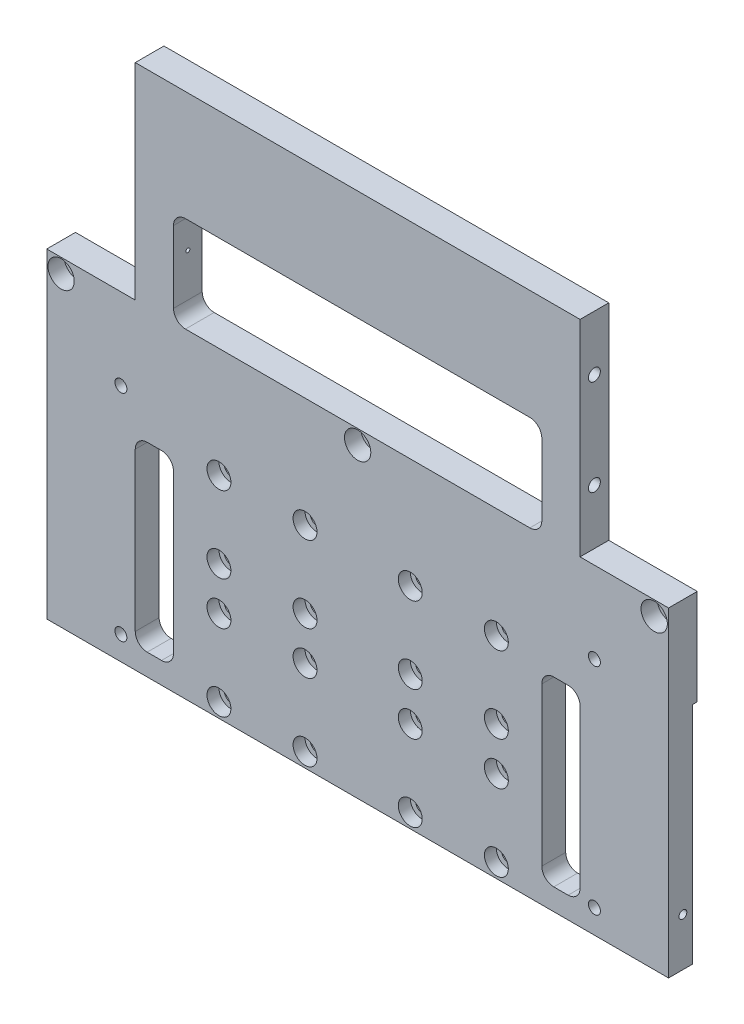
SolidWorks part; units mm, degrees
material "45#"
ref_plane "前视" through (0, 0, 0) normal (0, 0, 1) x (1, 0, 0)
ref_plane "上视" through (0, 0, 0) normal (0, 1, 0) x (1, 0, 0)
ref_plane "右视" through (0, 0, 0) normal (1, 0, 0) x (0, 0, -1)
sketch "草图1" plane through (0, 0, 0) normal (0, 0, 1) x (1, 0, 0)
  line L1 (-130, -110) -> (130, -110)
  line L2 (-130, -110) -> (-130, 110)
  line L3 (-130, 110) -> (130, 110)
  line L4 (130, -110) -> (130, 110)
  line L5 (-130, -110) -> (130, 110) construction
  line L6 (-130, 110) -> (130, -110) construction
  point P0 (0, 0)
  dimension "D1" = 260
  dimension "D2" = 220
extrude "凸台-拉伸1" add sketch "草图1" along normal blind 12
sketch "草图2" plane through (130, 0, 0) normal (1, 0, 0) x (0, 0, -1)
  line L1 (0, -110) -> (-2, -110)
  line L2 (0, -110) -> (0, -16)
  line L3 (0, -16) -> (-2, -16)
  line L4 (-2, -110) -> (-2, -16)
  dimension "D1" = 94
  dimension "D2" = 2
extrude "切除-拉伸1" cut sketch "草图2" against normal through all
hole_wizard "打孔尺寸根据内六角圆柱头螺钉的类型1" positions "草图4" profile "草图3" counterbore size "M5" standard "Gb" end condition through all
sketch "草图4" plane through (0, 0, 12) normal (0, 0, 1) x (1, 0, 0)
  line L0 (0, -16) -> (0, -63) construction
  line L1 (-130, -16) -> (130, -16) construction
  line L2 (0, -63) -> (-130, -63) construction
  line L3 (-130, 110) -> (-130, -110) construction
  point P0 (-58, -22)
  point P2 (-22, -22)
  point P4 (-22, -54)
  point P6 (-58, -54)
  point P20 (58, -54)
  point P21 (22, -54)
  point P22 (22, -22)
  point P23 (58, -22)
  point P24 (58, -104)
  point P25 (22, -104)
  point P26 (22, -72)
  point P27 (58, -72)
  point P28 (-58, -72)
  point P29 (-22, -72)
  point P30 (-22, -104)
  point P31 (-58, -104)
  dimension "D1" = 36
  dimension "D2" = 32
  dimension "D3" = 6
  dimension "D4" = 44
  dimension "D5" = 50
sketch "草图3" plane through (-58, -22, 12) normal (1, 0, 0) x (0, -1, 0)
  line L0 (0, 0) -> (0, 12)
  line L1 (0, 12) -> (2.75, 12)
  line L3 (2.75, 12) -> (2.75, 5)
  line L4 (2.75, 5) -> (5, 5)
  line L5 (5, 5) -> (5, 0)
  line L7 (5, 0) -> (0, 0)
  line L11 (0, -6.35) -> (0, 107.95) construction
  dimension "通孔孔直径" = 5.5
  dimension "通孔孔深度" = 12
  dimension "柱形沉头孔直径" = 10
  dimension "柱形沉头孔深度" = 5
hole_wizard "打孔尺寸根据内六角圆柱头螺钉的类型2" positions "草图6" profile "草图5" counterbore size "M6" standard "Gb" end condition through all
sketch "草图6" plane through (0, 0, 12) normal (0, 0, 1) x (1, 0, 0)
  line L0 (0, 110) -> (0, 24.5896) construction
  line L1 (130, 110) -> (-130, 110) construction
  line L2 (-130, 110) -> (-130, -110) construction
  line L3 (-130, -16) -> (130, -16) construction
  point P0 (-124, 18)
  point P9 (0, 18)
  point P12 (124, 18)
  dimension "D1" = 6
  dimension "D2" = 34
sketch "草图5" plane through (-124, 18, 12) normal (1, 0, 0) x (0, -1, 0)
  line L0 (0, 0) -> (0, 12)
  line L1 (0, 12) -> (3.3, 12)
  line L3 (3.3, 12) -> (3.3, 6.8)
  line L4 (3.3, 6.8) -> (5.5, 6.8)
  line L5 (5.5, 6.8) -> (5.5, 0)
  line L7 (5.5, 0) -> (0, 0)
  line L11 (0, -6.35) -> (0, 107.95) construction
  dimension "通孔孔直径" = 6.6
  dimension "通孔孔深度" = 12
  dimension "柱形沉头孔直径" = 11
  dimension "柱形沉头孔深度" = 6.8
sketch "草图7" plane through (0, 0, 12) normal (0, 0, 1) x (1, 0, 0)
  line L0 (0, 110) -> (0, 51.5525) construction
  line L1 (130, 110) -> (-130, 110) construction
  line L2 (93, 110) -> (93, 24)
  line L3 (-130, 110) -> (-93, 110)
  line L4 (-130, 110) -> (-130, 24)
  line L5 (-130, 24) -> (-93, 24)
  line L6 (-93, 110) -> (-93, 24)
  line L7 (130, 24) -> (93, 24)
  line L8 (130, 110) -> (130, 24)
  line L9 (130, 110) -> (93, 110)
  circle A0 centre (-124, 18) radius 5.5 construction
  dimension "D1" = 37
  dimension "D2" = 6
extrude "切除-拉伸2" cut sketch "草图7" against normal through all
hole_wizard "M6 螺纹孔1" positions "草图9" profile "草图8" tap size "M6" standard "Gb"
sketch "草图9" plane through (-93, 0, 0) normal (-1, 0, 0) x (0, 0, 1)
  line L0 (6, 110) -> (6, 67) construction
  line L1 (0, 110) -> (12, 110) construction
  line L2 (6, 67) -> (0, 67) construction
  line L3 (0, 24) -> (0, 110) construction
  point P0 (6, 87)
  point P14 (6, 47)
  dimension "D1" = 40
sketch "草图8" plane through (-93, 87, 6) normal (0, 1, 0) x (0, 0, 1)
  line L0 (0, 0) -> (0, 16.5022)
  line L1 (0, 16.5022) -> (2.5, 15)
  line L2 (2.5, 15) -> (2.5, 0)
  line L5 (2.5, 0) -> (0, 0)
  line L10 (0, 16.5022) -> (-2.5, 15) construction
  line L11 (0, -6.35) -> (0, 107.95) construction
  dimension "螺纹孔钻头直径" = 5
  dimension "螺纹孔钻头深度" = 15
  dimension "导头角度" = 118
cosmetic thread "孔螺蚊线1" parameters "D1"=12, "D2"=6
cosmetic thread "孔螺蚊线2" parameters "D1"=12, "D2"=6
mirror "镜向1" about plane through (0, 0, 0) normal (1, 0, 0) of "M6 螺纹孔1"
sketch "草图10" plane through (0, 0, 12) normal (0, 0, 1) x (1, 0, 0)
  line L0 (-22, -22) -> (22, -104) construction
  line L1 (-130, 24) -> (-93, 24) construction
  line L2 (-88, -101) -> (-82, -101)
  line L3 (-93, -96) -> (-93, -30)
  line L4 (-88, -25) -> (-82, -25)
  line L5 (-77, -96) -> (-77, -30)
  line L6 (-93, -101) -> (-77, -25) construction
  line L7 (-93, -25) -> (-77, -101) construction
  line L8 (-72, 64) -> (72, 64)
  line L9 (-77, 59) -> (-77, 29)
  line L10 (-72, 24) -> (72, 24)
  line L11 (77, 59) -> (77, 29)
  line L12 (-77, 64) -> (77, 24) construction
  line L13 (-77, 24) -> (77, 64) construction
  line L15 (0, -63) -> (0, -10.1951) construction
  line L16 (0, -63) -> (44.6809, -63) construction
  line L18 (93, -25) -> (77, -101) construction
  line L19 (93, -101) -> (77, -25) construction
  line L20 (77, -96) -> (77, -30)
  line L21 (88, -25) -> (82, -25)
  line L22 (93, -96) -> (93, -30)
  line L23 (88, -101) -> (82, -101)
  arc A0 (-82, -25) -> (-77, -30) centre (-82, -30) cw
  arc A1 (-82, -101) -> (-77, -96) centre (-82, -96) ccw
  arc A2 (-88, -101) -> (-93, -96) centre (-88, -96) cw
  arc A3 (-93, -30) -> (-88, -25) centre (-88, -30) cw
  circle A4 centre (22, -104) radius 5 construction
  circle A5 centre (-58, -72) radius 5 construction
  arc A6 (72, 64) -> (77, 59) centre (72, 59) cw
  arc A7 (72, 24) -> (77, 29) centre (72, 29) ccw
  arc A8 (-77, 29) -> (-72, 24) centre (-72, 29) ccw
  arc A9 (-72, 64) -> (-77, 59) centre (-72, 59) ccw
  arc A10 (93, -30) -> (88, -25) centre (88, -30) ccw
  arc A11 (88, -101) -> (93, -96) centre (88, -96) ccw
  arc A12 (82, -101) -> (77, -96) centre (82, -96) cw
  arc A13 (82, -25) -> (77, -30) centre (82, -30) ccw
  point P4 (-85, -63)
  point P25 (0, 44)
  point P66 (85, -63)
  dimension "D1" = 5
  dimension "D2" = 3
  dimension "D3" = 19
  dimension "D5" = 40
  dimension "D6" = 16
extrude "切除-拉伸3" cut sketch "草图10" against normal through all
hole_wizard "M6 螺纹孔2" positions "草图12" profile "草图11" tap size "M6" standard "Gb" end condition through all
sketch "草图12" plane through (0, 0, 12) normal (0, 0, 1) x (1, 0, 0)
  line L0 (-130, -110) -> (130, -110) construction
  line L1 (0, -110) -> (0, -142.6148) construction
  point P0 (-99, -10)
  point P2 (-99, -100)
  point P13 (99, -100)
  point P14 (99, -10)
  dimension "D1" = 90
  dimension "D2" = 10
  dimension "D3" = 198
sketch "草图11" plane through (-99, -10, 12) normal (1, 0, 0) x (0, -1, 0)
  line L0 (0, 0) -> (0, 12)
  line L1 (0, 12) -> (2.5, 12)
  line L2 (2.5, 12) -> (2.5, 0)
  line L5 (2.5, 0) -> (0, 0)
  line L11 (0, -6.35) -> (0, 107.95) construction
  dimension "通孔螺纹孔钻头直径" = 5
  dimension "通孔螺纹孔钻头深度" = 12
cosmetic thread "孔螺蚊线3" parameters "D2"=6
cosmetic thread "孔螺蚊线4" parameters "D2"=6
cosmetic thread "孔螺蚊线5" parameters "D2"=6
cosmetic thread "孔螺蚊线6" parameters "D2"=6
hole_wizard "M4 螺纹孔1" positions "草图14" profile "草图13" tap size "M4" standard "Gb"
sketch "草图14" plane through (-130, 0, 0) normal (-1, 0, 0) x (0, 0, 1)
  line L0 (12, -110) -> (2, -110) construction
  point P0 (6, -90)
  dimension "D1" = 20
sketch "草图13" plane through (-130, -90, 6) normal (0, 1, 0) x (0, 0, 1)
  line L0 (0, 0) -> (0, 11.0914)
  line L1 (0, 11.0914) -> (1.65, 10.1)
  line L2 (1.65, 10.1) -> (1.65, 0)
  line L5 (1.65, 0) -> (0, 0)
  line L10 (0, 11.0914) -> (-1.65, 10.1) construction
  line L11 (0, -6.35) -> (0, 107.95) construction
  dimension "螺纹孔钻头直径" = 3.3
  dimension "螺纹孔钻头深度" = 10.1
  dimension "导头角度" = 118
cosmetic thread "孔螺蚊线7" parameters "D1"=8, "D2"=4
mirror "镜向2" about plane through (0, 0, 0) normal (1, 0, 0) of "M4 螺纹孔1"
